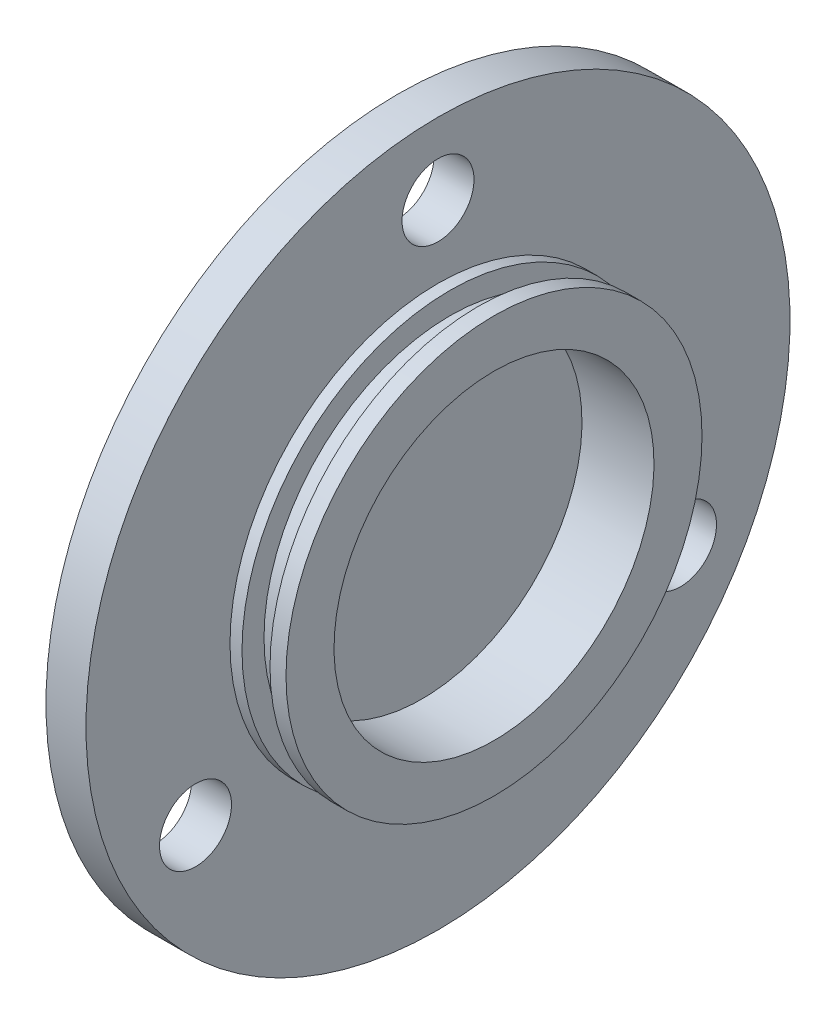
SolidWorks part; units mm, degrees
ref_plane "Piano frontale" through (0, 0, 0) normal (0, 0, 1) x (1, 0, 0)
ref_plane "Piano superiore" through (0, 0, 0) normal (0, 1, 0) x (1, 0, 0)
ref_plane "Piano destro" through (0, 0, 0) normal (1, 0, 0) x (0, 0, -1)
sketch "Schizzo1" plane through (0, 0, 0) normal (0, 0, 1) x (1, 0, 0)
  line L0 (0, 0) -> (0, 44)
  line L1 (0, 44) -> (5, 44)
  line L2 (5, 44) -> (5, 26)
  line L3 (5, 26) -> (6.5, 26)
  line L4 (12, 26) -> (12, 20)
  line L8 (12, 20) -> (3, 20)
  line L9 (3, 20) -> (3, 0)
  line L10 (3, 0) -> (0, 0)
  line L11 (6.5, 26) -> (6.5, 23.25)
  line L12 (6.5, 23.25) -> (10, 23.25)
  line L13 (10, 23.25) -> (10, 26)
  line L14 (10, 26) -> (12, 26)
  point P5 (12, 23)
  dimension "D1" = 5
  dimension "D2" = 9
  dimension "12" = 12
  dimension "D3" = 20
  dimension "D4" = 26
  dimension "D5" = 23.25
  dimension "D6" = 3.5
  dimension "D7" = 2
revolve "Rivoluzione1" add sketch "Schizzo1" angle 360 about L10
sketch "Schizzo2" plane through (5, 0, 0) normal (1, 0, 0) x (0, 0, -1)
  circle A0 centre (0, 35) radius 4.5
  circle A1 centre (0, 0) radius 26 construction
  circle A2 centre (30.3109, -17.5) radius 4.5
  circle A3 centre (-30.3109, -17.5) radius 4.5
  point P11 (0, 0)
  dimension "D1" = 9
  dimension "D2" = 35
  dimension "D3" = 3
extrude "Taglio-Estrusione1" cut sketch "Schizzo2" against normal through all
